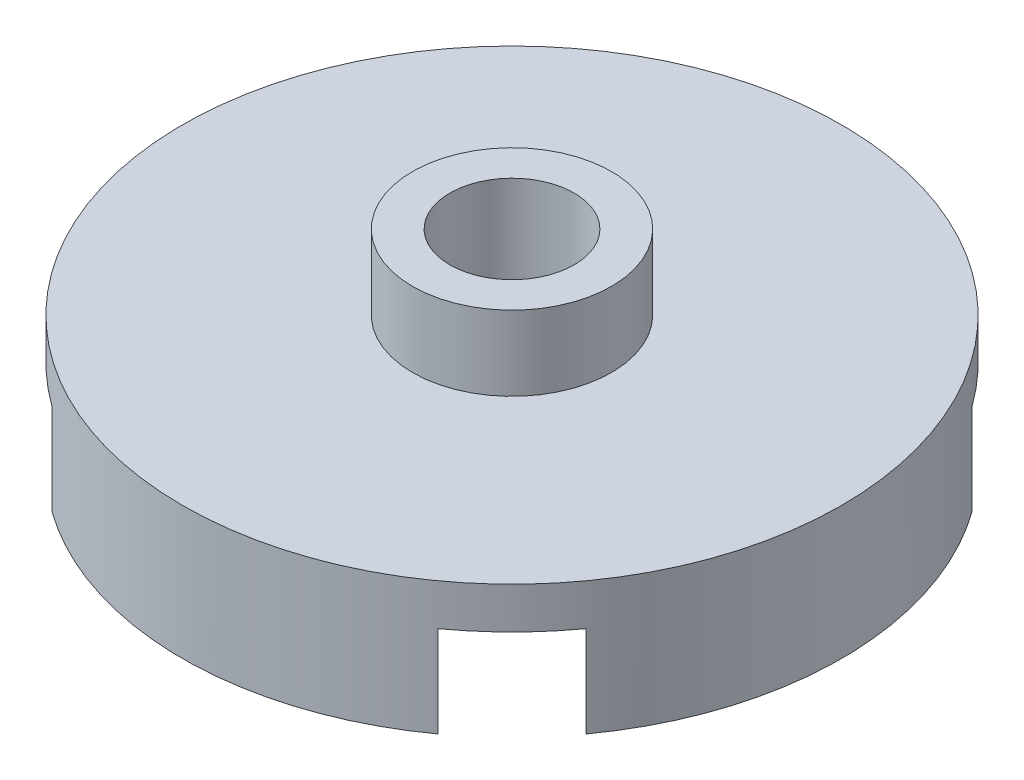
SolidWorks part; units mm, degrees
ref_plane "Front Plane" through (0, 0, 0) normal (0, 0, 1) x (1, 0, 0)
ref_plane "Top Plane" through (0, 0, 0) normal (0, 1, 0) x (1, 0, 0)
ref_plane "Right Plane" through (0, 0, 0) normal (1, 0, 0) x (0, 0, -1)
sketch "Sketch1" plane through (0, 0, 0) normal (0, 1, 0) x (1, 0, 0)
  line L1 (-7.95, -7.95) -> (7.95, -7.95) construction
  line L2 (-7.95, -7.95) -> (-7.95, 7.95) construction
  line L3 (-7.95, 7.95) -> (7.95, 7.95) construction
  line L4 (7.95, -7.95) -> (7.95, 7.95) construction
  line L5 (-7.95, -7.95) -> (7.95, 7.95) construction
  line L6 (-7.95, 7.95) -> (7.95, -7.95) construction
  circle A0 centre (0, 0) radius 7.95
  point P0 (0, 0)
  dimension "D1" = 15.9
extrude "Boss-Extrude1" add sketch "Sketch1" along normal blind 3.2
sketch "Sketch2" plane through (0, 3.2, 0) normal (0, 1, 0) x (1, 0, 0)
  circle A0 centre (0, 0) radius 2.4
  dimension "D1" = 4.8
extrude "Boss-Extrude2" add sketch "Sketch2" along normal blind 1.8
shell "Shell1" thickness 1
sketch "Sketch3" plane through (0, 2.2, 0) normal (0, -1, 0) x (1, 0, 0)
  line L1 (7.95, -7.95) -> (-7.95, -7.95) construction
  line L2 (7.95, -7.95) -> (7.95, 7.95) construction
  line L3 (7.95, 7.95) -> (-7.95, 7.95) construction
  line L4 (-7.95, -7.95) -> (-7.95, 7.95) construction
  line L5 (7.95, -7.95) -> (-7.95, 7.95) construction
  line L6 (7.95, 7.95) -> (-7.95, -7.95) construction
  circle A0 centre (0, 0) radius 7.95 construction
  circle A1 centre (0, 0) radius 3.3
  circle A2 centre (0, 0) radius 2.4
  point P0 (0, 0)
  dimension "D1" = 6.6
  dimension "D2" = 4.8
extrude "Boss-Extrude3" add sketch "Sketch3" along normal up to surface (2.2 mm away) up to face at (0, 0, 6.95)
sketch "Sketch4" plane through (0, 2.2, 0) normal (0, -1, 0) x (1, 0, 0)
  line L0 (4.8624, 4.8624) -> (4.8624, -4.8624) construction
  line L1 (-7.95, -7.95) -> (7.95, -7.95) construction
  line L2 (-7.95, -7.95) -> (-7.95, 7.95) construction
  line L3 (-7.95, 7.95) -> (7.95, 7.95) construction
  line L4 (7.95, -7.95) -> (7.95, 7.95) construction
  line L5 (-7.95, -7.95) -> (7.95, 7.95) construction
  line L6 (-7.95, 7.95) -> (7.95, -7.95) construction
  circle A0 centre (0, 0) radius 7.95 construction
  circle A3 centre (-4.0659, -4.0659) radius 2.45
  circle A4 centre (0, 0) radius 3.3 construction
  point P0 (0, 0)
  dimension "D2" = 4.9
extrude "Cut-Extrude1" cut sketch "Sketch4" along normal through all
pattern_circular "CirPattern2" count 4 over 360 about axis through (0, 0, 0) along (0, 1, 0) of "Cut-Extrude1"
sketch "Sketch5" plane through (0, 5, 0) normal (0, 1, 0) x (1, 0, 0)
  circle A0 centre (0, 0) radius 1.5
  circle A1 centre (0, 0) radius 2.4 construction
  dimension "D1" = 0.9
extrude "Cut-Extrude2" cut sketch "Sketch5" against normal through all
